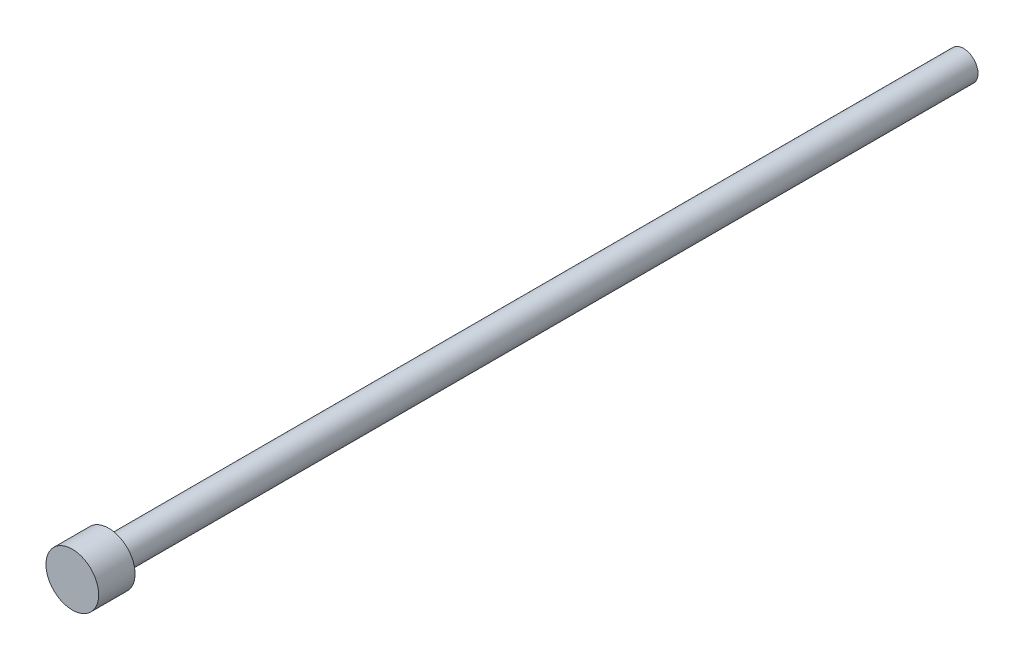
SolidWorks part; units mm, degrees
ref_plane "Front Plane" through (0, 0, 0) normal (0, 0, 1) x (1, 0, 0)
ref_plane "Top Plane" through (0, 0, 0) normal (0, 1, 0) x (1, 0, 0)
ref_plane "Right Plane" through (0, 0, 0) normal (1, 0, 0) x (0, 0, -1)
sketch "Sketch2" plane through (0, 0, 0) normal (0, 0, 1) x (1, 0, 0)
  circle A0 centre (0, 0) radius 2.0383
  dimension "D1" = 4.0767
extrude "Boss-Extrude1" add sketch "Sketch2" along normal blind 119.38 contours A0
sketch "Sketch3" plane through (0, 0, 119.38) normal (0, 0, 1) x (1, 0, 0)
  circle A0 centre (0, 0) radius 3.683
extrude "Boss-Extrude2" add sketch "Sketch3" along normal blind 5.08
